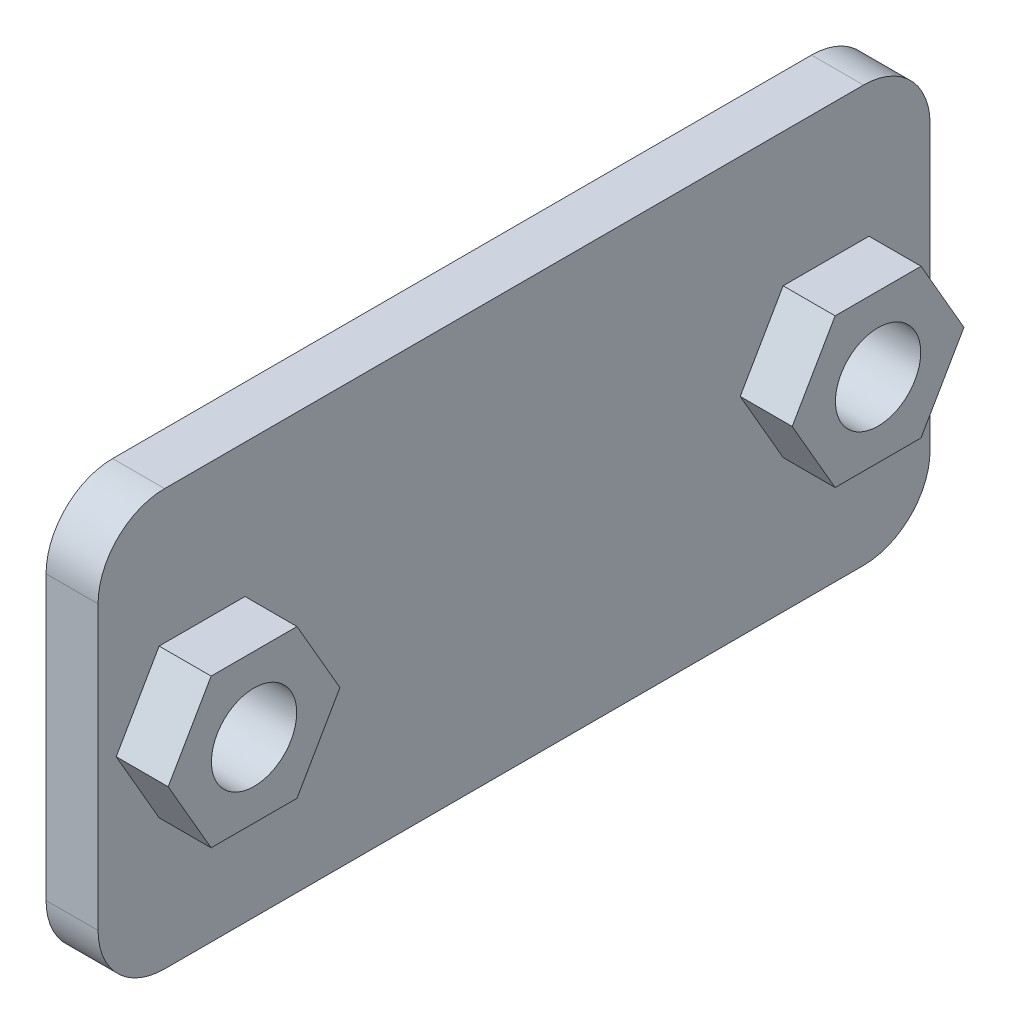
SolidWorks part; units mm, degrees
ref_plane "Płaszczyzna przednia" through (0, 0, 0) normal (0, 0, 1) x (1, 0, 0)
ref_plane "Płaszczyzna górna" through (0, 0, 0) normal (0, 1, 0) x (1, 0, 0)
ref_plane "Płaszczyzna prawa" through (0, 0, 0) normal (1, 0, 0) x (0, 0, -1)
sketch "Szkic2" plane through (0, 0, 0) normal (1, 0, 0) x (0, 0, -1)
  line L1 (-40, 20) -> (40, 20)
  line L2 (-40, 20) -> (-40, -20)
  line L3 (-40, -20) -> (40, -20)
  line L4 (40, 20) -> (40, -20)
  line L5 (-40, 20) -> (40, -20) construction
  line L6 (-40, -20) -> (40, 20) construction
  point P0 (0, 0)
  dimension "D1" = 80
  dimension "D2" = 40
extrude "Dodanie-wyciągnięcie1" add sketch "Szkic2" along normal blind 5
fillet "Zaokrąglenie1" radius 6.4 4 edges at (2.5, 20, -40) (2.5, -20, -40) (2.5, -20, 40) (2.5, 20, 40)
sketch "Szkic3" plane through (5, 0, 0) normal (1, 0, 0) x (0, 0, -1)
  line L0 (2.75, 0) -> (-2.75, 0) construction
  circle A0 centre (-30, 0) radius 4.1
  circle A1 centre (30, 0) radius 4.1
  dimension "D1" = 8.2
  dimension "D2" = 8.2
  dimension "D3" = 30
  dimension "D4" = 30
extrude "Wytnij-wyciągnięcie1" cut sketch "Szkic3" against normal mid plane 20
sketch "Szkic4" plane through (5, 0, 0) normal (1, 0, 0) x (0, 0, -1)
  line L1 (-21.7439, 0) -> (-25.8719, 7.15)
  line L2 (-25.8719, 7.15) -> (-34.1281, 7.15)
  line L3 (-34.1281, 7.15) -> (-38.2561, 0)
  line L4 (-38.2561, 0) -> (-34.1281, -7.15)
  line L5 (-34.1281, -7.15) -> (-25.8719, -7.15)
  line L6 (-25.8719, -7.15) -> (-21.7439, 0)
  line L7 (21.7439, 0) -> (25.8719, -7.15)
  line L8 (25.8719, -7.15) -> (34.1281, -7.15)
  line L9 (34.1281, -7.15) -> (38.2561, 0)
  line L10 (38.2561, 0) -> (34.1281, 7.15)
  line L11 (34.1281, 7.15) -> (25.8719, 7.15)
  line L12 (25.8719, 7.15) -> (21.7439, 0)
  circle A0 centre (-30, 0) radius 7.15 construction
  circle A1 centre (30, 0) radius 7.15 construction
  dimension "D1" = 14.3
  dimension "D2" = 14.3
extrude "Dodanie-wyciągnięcie2" add sketch "Szkic4" along normal blind 5
sketch "Szkic5" plane through (0, 0, 0) normal (-1, 0, 0) x (0, 0, 1)
  circle A0 centre (30, 0) radius 4.1
  circle A1 centre (-30, 0) radius 4.1
extrude "Wytnij-wyciągnięcie2" cut sketch "Szkic5" against normal blind 15
